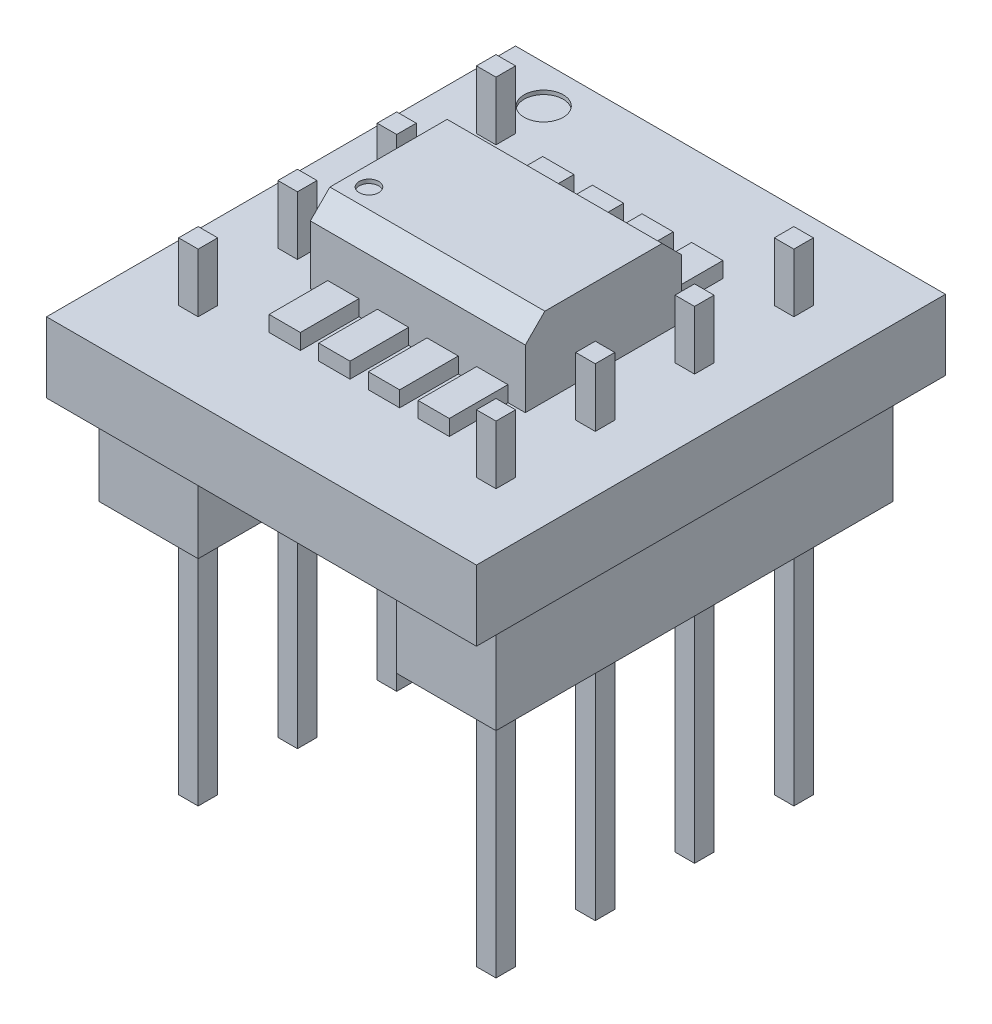
SolidWorks part; units mm, degrees
ref_plane "Front Plane" through (0, 0, 0) normal (0, 0, 1) x (1, 0, 0)
ref_plane "Top Plane" through (0, 0, 0) normal (0, 1, 0) x (1, 0, 0)
ref_plane "Right Plane" through (0, 0, 0) normal (1, 0, 0) x (0, 0, -1)
sketch "Sketch1" plane through (0, 0, 0) normal (0, 1, 0) x (1, 0, 0)
  line L1 (-5.5, -6) -> (5.5, -6)
  line L2 (-5.5, -6) -> (-5.5, 6)
  line L3 (-5.5, 6) -> (5.5, 6)
  line L4 (5.5, -6) -> (5.5, 6)
  line L5 (-5.5, -6) -> (5.5, 6) construction
  line L6 (-5.5, 6) -> (5.5, -6) construction
  point P0 (0, 0)
  dimension "D1" = 11
  dimension "D2" = 12
extrude "Boss-Extrude1" add sketch "Sketch1" along normal blind 1.8
sketch "Sketch2" plane through (0, 0, 0) normal (0, -1, 0) x (1, 0, 0)
  line L1 (-5.5, 0) -> (5.5, 0) construction
  line L2 (-5.5, -6) -> (-5.5, 6) construction
  line L3 (5.5, 6) -> (5.5, -6) construction
  line L4 (-2.54, 5.08) -> (2.54, 5.08) construction
  line L5 (-5.08, -5.08) -> (-2.54, -5.08)
  line L6 (-5.08, -5.08) -> (-5.08, 5.08)
  line L7 (-5.08, 5.08) -> (-2.54, 5.08)
  line L8 (-2.54, -5.08) -> (-2.54, 5.08)
  line L9 (-5.08, -5.08) -> (-2.54, 5.08) construction
  line L10 (-5.08, 5.08) -> (-2.54, -5.08) construction
  line L11 (2.54, -5.08) -> (5.08, -5.08)
  line L12 (2.54, -5.08) -> (2.54, 5.08)
  line L13 (2.54, 5.08) -> (5.08, 5.08)
  line L14 (5.08, -5.08) -> (5.08, 5.08)
  line L15 (2.54, -5.08) -> (5.08, 5.08) construction
  line L16 (2.54, 5.08) -> (5.08, -5.08) construction
  line L17 (0, 5.08) -> (0, 0) construction
  point P0 (-3.81, 0)
  point P11 (3.81, 0)
  dimension "D1" = 2.54
  dimension "D2" = 10.16
  dimension "D3" = 10.16
extrude "Boss-Extrude2" add sketch "Sketch2" along normal blind 2.54
sketch "Sketch3" plane through (0, -2.54, 0) normal (0, -1, 0) x (1, 0, 0)
  line L0 (3.81, 5.08) -> (3.81, -5.08) construction
  line L1 (5.08, 5.08) -> (2.54, 5.08) construction
  line L2 (2.54, -5.08) -> (5.08, -5.08) construction
  line L3 (3.56, 1.52) -> (4.06, 1.52)
  line L4 (3.56, 4.06) -> (4.06, 4.06)
  line L5 (3.56, 4.06) -> (3.56, 3.56)
  line L6 (3.56, 3.56) -> (4.06, 3.56)
  line L7 (4.06, 4.06) -> (4.06, 3.56)
  line L8 (3.56, 4.06) -> (4.06, 3.56) construction
  line L9 (3.56, 3.56) -> (4.06, 4.06) construction
  line L10 (4.06, 1.52) -> (4.06, 1.02)
  line L11 (3.56, 1.02) -> (4.06, 1.02)
  line L12 (3.56, 1.52) -> (3.56, 1.02)
  line L13 (3.56, 1.02) -> (4.06, 1.52) construction
  line L14 (3.56, 1.52) -> (4.06, 1.02) construction
  line L15 (3.56, -1.02) -> (4.06, -1.02)
  line L16 (4.06, -1.02) -> (4.06, -1.52)
  line L17 (3.56, -1.52) -> (4.06, -1.52)
  line L18 (3.56, -1.02) -> (3.56, -1.52)
  line L19 (3.56, -1.52) -> (4.06, -1.02) construction
  line L20 (3.56, -1.02) -> (4.06, -1.52) construction
  line L21 (3.56, -3.56) -> (4.06, -3.56)
  line L22 (4.06, -3.56) -> (4.06, -4.06)
  line L23 (3.56, -4.06) -> (4.06, -4.06)
  line L24 (3.56, -3.56) -> (3.56, -4.06)
  line L25 (3.56, -4.06) -> (4.06, -3.56) construction
  line L26 (3.56, -3.56) -> (4.06, -4.06) construction
  line L27 (3.56, 4.06) -> (3.56, 5.08) construction
  line L28 (5.08, 5.08) -> (2.54, 5.08) construction
  line L29 (3.56, -4.06) -> (3.56, -5.08) construction
  point P6 (3.81, 3.81)
  dimension "D2" = 0.5
  dimension "D3" = 2.54
  dimension "D1" = 4
extrude "Boss-Extrude3" add sketch "Sketch3" along normal blind 6.5 and the other way offset from surface (5.84 mm away) 1.5 other way up to face at (0, 1.8, 0)
mirror "Mirror1" about plane through (0, 0, 0) normal (1, 0, 0) of "Boss-Extrude3"
sketch "Sketch4" plane through (0, 1.8, 0) normal (0, 1, 0) x (1, 0, 0)
  line L1 (-2.75, -2) -> (2.75, -2)
  line L2 (-2.75, -2) -> (-2.75, 2)
  line L3 (-2.75, 2) -> (2.75, 2)
  line L4 (2.75, -2) -> (2.75, 2)
  line L5 (-2.75, -2) -> (2.75, 2) construction
  line L6 (-2.75, 2) -> (2.75, -2) construction
  point P0 (0, 0)
  dimension "D1" = 4
  dimension "D2" = 5.5
extrude "Boss-Extrude4" add sketch "Sketch4" along normal blind 2
chamfer "Chamfer1" distance 0.5 angle 45 2 edges at (0, 3.8, -2) (0, 3.8, 2)
sketch "Sketch5" plane through (0, 1.8, 0) normal (0, 1, 0) x (1, 0, 0)
  line L0 (-2.75, 0) -> (2.75, 0) construction
  line L1 (-2.75, 2) -> (-2.75, -2) construction
  line L2 (2.75, -1.5) -> (2.75, 1.5) construction
  line L3 (-0.235, -3.5) -> (-0.235, 3.5)
  line L4 (-2.305, -3.5) -> (-1.505, -3.5)
  line L5 (-2.305, -3.5) -> (-2.305, 3.5)
  line L6 (-2.305, 3.5) -> (-1.505, 3.5)
  line L7 (-1.505, -3.5) -> (-1.505, 3.5)
  line L8 (-2.305, -3.5) -> (-1.505, 3.5) construction
  line L9 (-2.305, 3.5) -> (-1.505, -3.5) construction
  line L10 (-1.035, 3.5) -> (-0.235, 3.5)
  line L11 (-1.035, -3.5) -> (-1.035, 3.5)
  line L12 (-1.035, -3.5) -> (-0.235, -3.5)
  line L13 (-1.035, -3.5) -> (-0.235, 3.5) construction
  line L14 (-1.035, 3.5) -> (-0.235, -3.5) construction
  line L15 (1.035, -3.5) -> (1.035, 3.5)
  line L16 (0.235, 3.5) -> (1.035, 3.5)
  line L17 (0.235, -3.5) -> (0.235, 3.5)
  line L18 (0.235, -3.5) -> (1.035, -3.5)
  line L19 (0.235, -3.5) -> (1.035, 3.5) construction
  line L20 (0.235, 3.5) -> (1.035, -3.5) construction
  line L21 (2.305, -3.5) -> (2.305, 3.5)
  line L22 (1.505, 3.5) -> (2.305, 3.5)
  line L23 (1.505, -3.5) -> (1.505, 3.5)
  line L24 (1.505, -3.5) -> (2.305, -3.5)
  line L25 (1.505, -3.5) -> (2.305, 3.5) construction
  line L26 (1.505, 3.5) -> (2.305, -3.5) construction
  line L27 (-2.305, 3.5) -> (-2.75, 2) construction
  line L28 (2.305, 3.5) -> (2.75, 2) construction
  line L29 (2.75, 2) -> (-2.75, 2) construction
  point P6 (-1.905, 0)
  dimension "D1" = 0.8
  dimension "D3" = 1.27
  dimension "D4" = 1.5
  dimension "D2" = 4
extrude "Boss-Extrude5" add sketch "Sketch5" along normal blind 0.4
sketch "Sketch6" plane through (0, 1.8, 0) normal (0, 1, 0) x (1, 0, 0)
  line L0 (-3.81, 4.06) -> (-3.81, 6) construction
  line L1 (-4.06, 4.06) -> (-3.56, 4.06) construction
  line L2 (5.5, 6) -> (-5.5, 6) construction
  circle A0 centre (-3.81, 5.03) radius 0.5
  point P9 (-3.81, 5.03)
  dimension "D1" = 1
extrude "Cut-Extrude1" cut sketch "Sketch6" against normal blind 0.1
sketch "Sketch7" plane through (0, 3.8, 0) normal (0, 1, 0) x (1, 0, 0)
  line L0 (-2.75, 2) -> (-2.75, -2) construction
  line L1 (-2.75, -1.5) -> (2.75, -1.5) construction
  circle A0 centre (-2.25, -1) radius 0.25
  dimension "D1" = 0.5
  dimension "D2" = 0.5
  dimension "D3" = 0.5
extrude "Cut-Extrude2" cut sketch "Sketch7" against normal blind 0.1
sketch "Sketch8" plane through (0, 3.8, 0) normal (0, 1, 0) x (1, 0, 0)
  circle A0 centre (0, 0) radius 1
  dimension "D1" = 2
